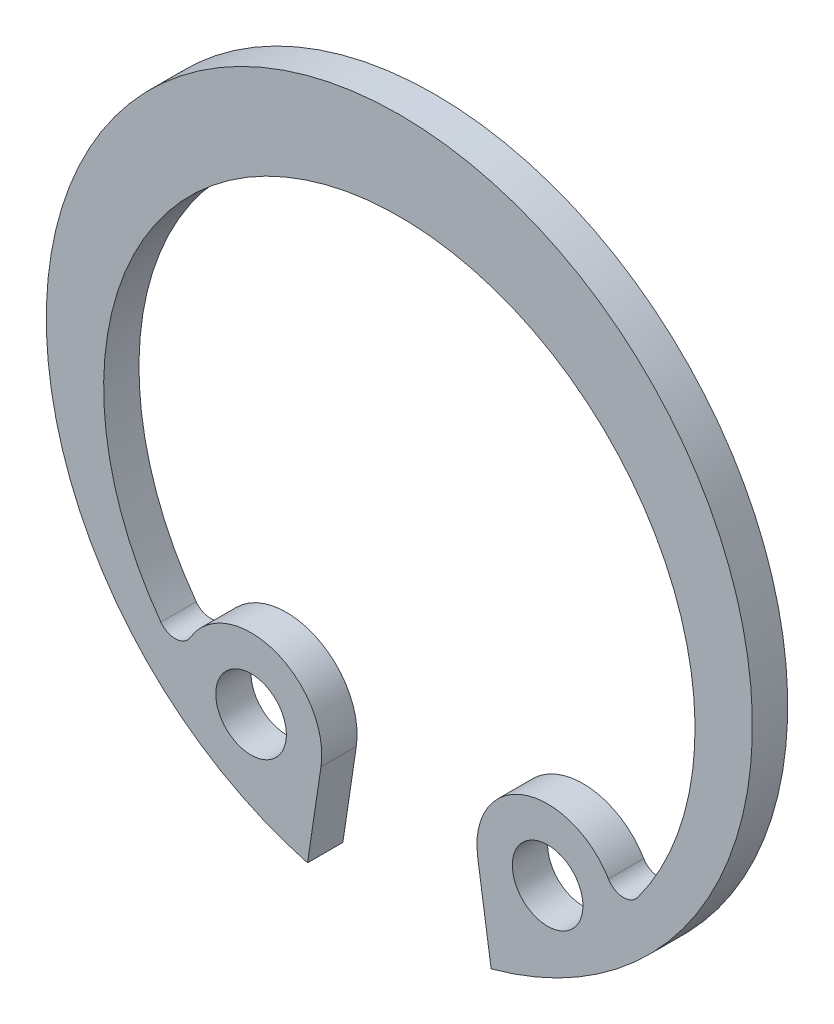
SolidWorks part; units mm, degrees
ref_plane "Front Plane" through (0, 0, 0) normal (0, 0, 1) x (1, 0, 0)
ref_plane "Top Plane" through (0, 0, 0) normal (0, 1, 0) x (1, 0, 0)
ref_plane "Right Plane" through (0, 0, 0) normal (1, 0, 0) x (0, 0, -1)
sketch "Sketch1" plane through (0, 0, 0) normal (0, 0, 1) x (1, 0, 0)
  line L0 (0, 0) -> (0, 10) construction
  line L1 (-2.2192, -7.1081) -> (-2.6, -9.6561)
  line L2 (2.2192, -7.1081) -> (2.6, -9.6561)
  line L3 (3.1489, -5.1073) -> (5.2482, -8.5122) construction
  arc A0 (2.6, -9.6561) -> (-2.6, -9.6561) centre (0, 0) ccw
  arc A1 (-6.7538, -5.8275) -> (-5.9209, -5.7876) centre (-6.3506, -5.5318) ccw
  circle A2 centre (-4.2, -6.8121) radius 1
  circle A3 centre (4.2, -6.8121) radius 1
  circle A4 centre (0, 0) radius 5.5 construction
  arc A6 (-2.2192, -7.1081) -> (-5.9209, -5.7876) centre (-4.2, -6.8121) ccw
  arc A7 (5.9209, -5.7876) -> (2.2192, -7.1081) centre (4.2, -6.8121) ccw
  arc A8 (6.7538, -5.8275) -> (-6.7538, -5.8275) centre (0, -0.875) ccw
  arc A9 (6.7538, -5.8275) -> (5.9209, -5.7876) centre (6.3506, -5.5318) cw
  point P13 (0, 7.5)
  dimension "D1" = 0.5
  dimension "RIC_D2_s" = 20
  dimension "D2" = 17
  dimension "RIC_D4_s" = 16.75
  dimension "RIC_D0_s" = 2
  dimension "RIC_D5_s" = 11
  dimension "RIC_B_s" = 2.5
  dimension "RIC_MSM_2" = 8.4
  dimension "RIC_MSM_1" = 5.2
  dimension "RIC_A_s" = 4
extrude "Boss-Extrude1" add sketch "Sketch1" along normal blind 1
equation "\"RIC_D4_s@Sketch1\"=\"RIC_D2_s@Sketch1\"-1.3*\"RIC_B_s@Sketch1\""
